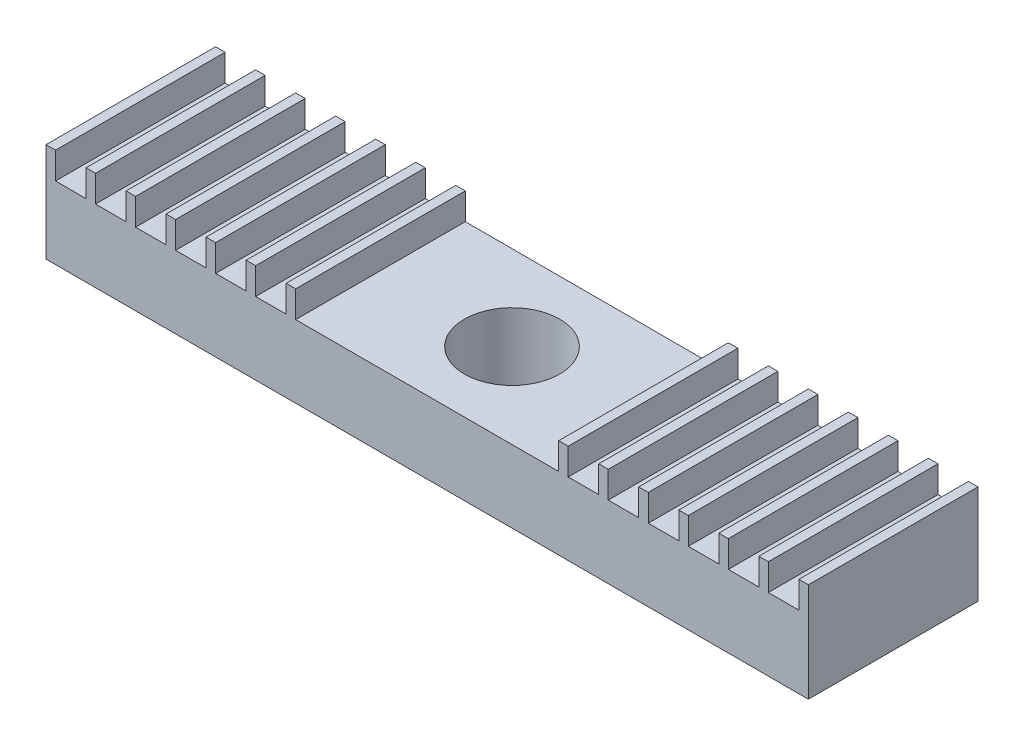
SolidWorks part; units mm, degrees
ref_plane "Front Plane" through (0, 0, 0) normal (0, 0, 1) x (1, 0, 0)
ref_plane "Top Plane" through (0, 0, 0) normal (0, 1, 0) x (1, 0, 0)
ref_plane "Right Plane" through (0, 0, 0) normal (1, 0, 0) x (0, 0, -1)
sketch "Sketch1" plane through (0, 0, 0) normal (0, 0, 1) x (1, 0, 0)
  line L0 (-20, 0) -> (0, 0)
  line L1 (0, 0) -> (0, 3.8)
  line L2 (0, 3.8) -> (-20, 3.8)
  line L3 (-20, 3.8) -> (-20, 0)
  dimension "D1" = 20
  dimension "D2" = 3.8
extrude "Boss-Extrude1" add sketch "Sketch1" along normal mid plane 8.9
sketch "Sketch2" plane through (0, 3.8, 0) normal (0, 1, 0) x (1, 0, 0)
  line L0 (0, -4.45) -> (-20, -4.45) construction
  line L1 (-20, 4.45) -> (-19.5, 4.45)
  line L2 (-20, 4.45) -> (-20, -4.45)
  line L3 (-20, -4.45) -> (-19.5, -4.45)
  line L4 (-19.5, 4.45) -> (-19.5, -4.45)
  dimension "D1" = 0.5
extrude "Boss-Extrude2" add sketch "Sketch2" along normal blind 1.4
pattern_linear "LPattern1" count 7 spacing 2.1 along (1, 0, 0) of "Boss-Extrude2"
mirror "Mirror1" about plane through (0, 0, 4.45) normal (-1, 0, 0) of bodies 103
sketch "Sketch3" plane through (0, 3.8, 0) normal (0, 1, 0) x (1, 0, 0)
  circle A0 centre (0, 0) radius 2.5
  dimension "D1" = 5
extrude "Cut-Extrude1" cut sketch "Sketch3" against normal through all
